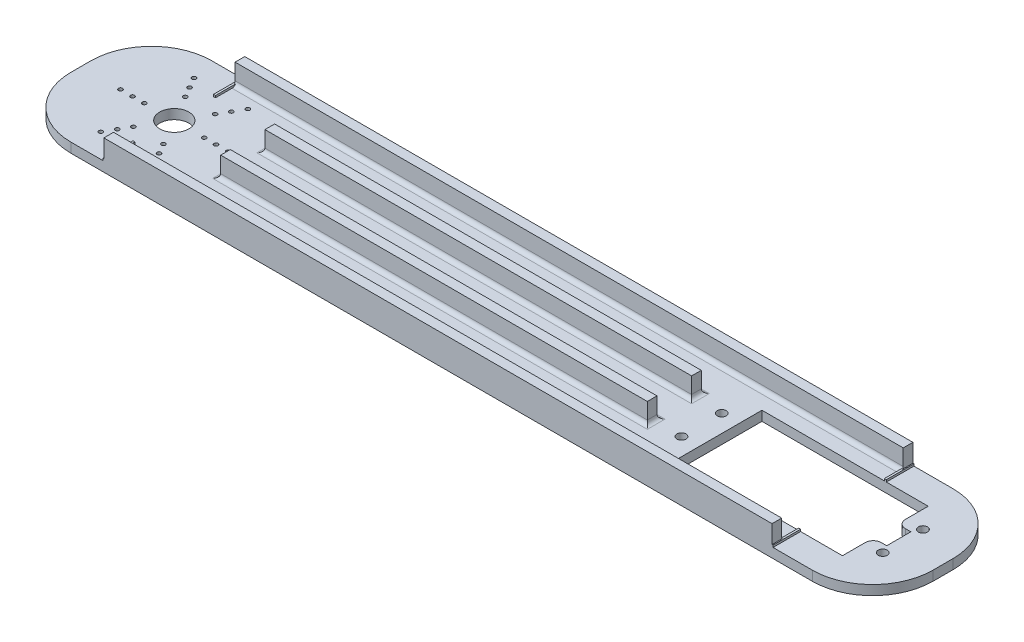
SolidWorks part; units mm, degrees
ref_plane "Front Plane" through (0, 0, 0) normal (0, 0, 1) x (1, 0, 0)
ref_plane "Top Plane" through (0, 0, 0) normal (0, 1, 0) x (1, 0, 0)
ref_plane "Right Plane" through (0, 0, 0) normal (1, 0, 0) x (0, 0, -1)
sketch "Sketch1" plane through (0, 0, 0) normal (0, 1, 0) x (1, 0, 0)
  line L1 (-86.6771, 38.9958) -> (127.5229, 38.9958)
  line L2 (-86.6771, 38.9958) -> (-86.6771, 3.9958)
  line L3 (-86.6771, 3.9958) -> (127.5229, 3.9958)
  line L4 (127.5229, 38.9958) -> (127.5229, 3.9958)
  dimension "D1" = 214.2
  dimension "D2" = 35
extrude "Boss-Extrude1" add sketch "Sketch1" along normal blind 2.4
sketch "Sketch2" plane through (0, 2.4, 0) normal (0, 1, 0) x (1, 0, 0)
  line L0 (-63.4771, 38.9958) -> (-63.4771, 2.4158) construction
  line L1 (127.5229, 38.9958) -> (-86.6771, 38.9958) construction
  line L2 (-86.6771, 21.4958) -> (127.5229, 21.4958) construction
  line L3 (-86.6771, 38.9958) -> (-86.6771, 3.9958) construction
  line L4 (127.5229, 3.9958) -> (127.5229, 38.9958) construction
  line L5 (112.5229, 38.9958) -> (112.5229, 3.9958) construction
  line L6 (-86.6771, 3.9958) -> (127.5229, 3.9958) construction
  line L7 (72.5229, 38.9958) -> (72.5229, 3.9958) construction
  line L9 (72.5229, 31.4958) -> (112.5229, 31.4958)
  line L10 (72.5229, 31.4958) -> (72.5229, 11.4958)
  line L11 (72.5229, 11.4958) -> (112.5229, 11.4958)
  line L12 (112.5229, 31.4958) -> (112.5229, 11.4958)
  circle A0 centre (67.5229, 26.4958) radius 1.13
  circle A1 centre (117.5229, 26.4958) radius 1.13
  circle A2 centre (117.5229, 16.4958) radius 1.13
  circle A3 centre (67.5229, 16.4958) radius 1.13
  circle A4 centre (-63.4771, 21.4958) radius 3.625
  circle A5 centre (-70.9071, 21.4958) radius 0.5
  circle A6 centre (-73.8421, 21.4958) radius 0.5
  circle A7 centre (-76.8471, 21.4958) radius 0.5
  circle A8 centre (-70.1621, 33.0745) radius 0.5
  circle A9 centre (-68.6596, 30.4721) radius 0.5
  circle A10 centre (-67.1921, 27.9303) radius 0.5
  circle A11 centre (-56.7921, 33.0745) radius 0.5
  circle A12 centre (-58.2946, 30.4721) radius 0.5
  circle A13 centre (-59.7621, 27.9303) radius 0.5
  circle A14 centre (-50.1071, 21.4958) radius 0.5
  circle A15 centre (-53.1121, 21.4958) radius 0.5
  circle A16 centre (-56.0471, 21.4958) radius 0.5
  circle A17 centre (-56.7921, 9.917) radius 0.5
  circle A18 centre (-58.2946, 12.5194) radius 0.5
  circle A19 centre (-59.7621, 15.0612) radius 0.5
  circle A20 centre (-70.1621, 9.917) radius 0.5
  circle A21 centre (-68.6596, 12.5194) radius 0.5
  circle A22 centre (-67.1921, 15.0612) radius 0.5
  point P24 (-63.4771, 21.4958)
  point P37 (-86.6771, 21.4958)
  point P39 (-63.4771, 21.4958)
  point P71 (-63.4771, 21.4958)
  dimension "D5" = 2.26
  dimension "D6" = 2.26
  dimension "D11" = 7.25
  dimension "D12" = 7.43
  dimension "D13" = 10.365
  dimension "D14" = 13.37
  dimension "D15" = 1
  dimension "D16" = 1
  dimension "D17" = 1
  dimension "D19" = 20
  dimension "D1" = 23.2
  dimension "D2" = 15
  dimension "D3" = 40
  dimension "D4" = 10
  dimension "D7" = 5
  dimension "D8" = 5
  dimension "D9" = 5
  dimension "D10" = 5
  dimension "D18" = 6
extrude "Cut-Extrude1" cut sketch "Sketch2" against normal blind 2.4
sketch "Sketch4" plane through (0, 2.4, 0) normal (0, 1, 0) x (1, 0, 0)
  line L0 (72.5229, 21.4958) -> (127.5229, 21.4958) construction
  line L1 (72.5229, 31.4958) -> (72.5229, 11.4958) construction
  line L2 (127.5229, 3.9958) -> (127.5229, 38.9958) construction
  line L3 (112.5229, 11.4958) -> (112.5229, 31.4958) construction
  line L4 (112.5229, 24.4958) -> (116.5229, 24.4958)
  line L5 (112.5229, 24.4958) -> (112.5229, 18.4958)
  line L6 (112.5229, 18.4958) -> (116.5229, 18.4958)
  line L7 (116.5229, 24.4958) -> (116.5229, 18.4958)
  dimension "D1" = 6
  dimension "D2" = 3
  dimension "D3" = 4
extrude "Cut-Extrude2" cut sketch "Sketch4" against normal blind 2.4
sketch "Sketch5" plane through (0, 2.4, 0) normal (0, 1, 0) x (1, 0, 0)
  line L0 (-63.4771, 21.4958) -> (127.5229, 21.4958) construction
  line L1 (127.5229, 3.9958) -> (127.5229, 38.9958) construction
  line L2 (-63.4771, 38.9958) -> (-63.4771, 3.9958) construction
  line L3 (127.5229, 38.9958) -> (-86.6771, 38.9958) construction
  line L4 (-86.6771, 3.9958) -> (127.5229, 3.9958) construction
  line L5 (102.5229, 38.9958) -> (102.5229, 3.9958) construction
  line L6 (112.5229, 31.4958) -> (72.5229, 31.4958) construction
  line L7 (102.2729, 38.9958) -> (102.7729, 38.9958)
  line L8 (102.2729, 38.9958) -> (102.2729, 31.4958)
  line L9 (102.2729, 31.4958) -> (102.7729, 31.4958)
  line L10 (102.7729, 38.9958) -> (102.7729, 31.4958)
  line L11 (102.7729, 3.9958) -> (102.7729, 11.4958)
  line L12 (102.2729, 11.4958) -> (102.7729, 11.4958)
  line L13 (102.2729, 3.9958) -> (102.2729, 11.4958)
  line L14 (102.2729, 3.9958) -> (102.7729, 3.9958)
  line L15 (-63.2271, 3.9958) -> (-63.2271, 11.4958)
  line L16 (-63.7271, 38.9958) -> (-63.2271, 38.9958)
  line L17 (-63.7271, 38.9958) -> (-63.7271, 31.4958)
  line L18 (-63.7271, 31.4958) -> (-63.2271, 31.4958)
  line L19 (-63.2271, 38.9958) -> (-63.2271, 31.4958)
  line L20 (-63.7271, 11.4958) -> (-63.2271, 11.4958)
  line L21 (-63.7271, 3.9958) -> (-63.7271, 11.4958)
  line L22 (-63.7271, 3.9958) -> (-63.2271, 3.9958)
  dimension "D1" = 166
  dimension "D2" = 0.5
  dimension "D3" = 0.25
  dimension "D4" = 0.25
  dimension "D5" = 0.5
  dimension "D6" = 7.5
extrude "Boss-Extrude2" add sketch "Sketch5" along normal blind 0.5
sketch "Sketch7" plane through (0, 2.4, 0) normal (0, 1, 0) x (1, 0, 0)
  line L0 (71.8729, 32.1458) -> (71.8729, 10.8458)
  line L1 (72.5229, 31.4958) -> (112.5229, 31.4958)
  line L2 (72.5229, 31.4958) -> (72.5229, 11.4958)
  line L3 (72.5229, 11.4958) -> (112.5229, 11.4958)
  line L4 (112.5229, 31.4958) -> (112.5229, 11.4958)
  line L5 (71.8729, 10.8458) -> (113.1729, 10.8458)
  line L6 (113.1729, 32.1458) -> (113.1729, 10.8458)
  line L7 (71.8729, 32.1458) -> (113.1729, 32.1458)
  dimension "D1" = 0.65
extrude "Cut-Extrude3" cut sketch "Sketch7" against normal through all both and the other way through all
sketch "Sketch8" plane through (0, 2.4, 0) normal (0, 1, 0) x (1, 0, 0)
  line L0 (102.5229, 38.9958) -> (102.5229, 3.9958) construction
  line L1 (-63.4771, 38.9958) -> (102.5229, 38.9958)
  line L2 (-63.4771, 38.9958) -> (-63.4771, 36.5958)
  line L3 (-63.4771, 36.5958) -> (102.5229, 36.5958)
  line L4 (102.5229, 38.9958) -> (102.5229, 36.5958)
  line L5 (-45.2566, 3.9958) -> (-45.2566, 38.9958) construction
  line L6 (-63.2271, 3.9958) -> (102.2729, 3.9958) construction
  line L7 (-63.4771, 21.4958) -> (116.5229, 21.4958) construction
  line L8 (-45.2566, 28.1958) -> (60.7434, 28.1958)
  line L9 (-45.2566, 28.1958) -> (-45.2566, 25.7958)
  line L10 (-45.2566, 25.7958) -> (60.7434, 25.7958)
  line L11 (60.7434, 28.1958) -> (60.7434, 25.7958)
  line L12 (116.5229, 18.4958) -> (116.5229, 24.4958) construction
  line L13 (60.7434, 14.7958) -> (60.7434, 17.1958)
  line L14 (-45.2566, 17.1958) -> (60.7434, 17.1958)
  line L15 (-45.2566, 14.7958) -> (-45.2566, 17.1958)
  line L16 (-45.2566, 14.7958) -> (60.7434, 14.7958)
  line L17 (102.5229, 3.9958) -> (102.5229, 6.3958)
  line L18 (-63.4771, 6.3958) -> (102.5229, 6.3958)
  line L19 (-63.4771, 3.9958) -> (-63.4771, 6.3958)
  line L20 (-63.4771, 3.9958) -> (102.5229, 3.9958)
  dimension "D1" = 2.4
  dimension "D2" = 2.4
  dimension "D3" = 106
  dimension "D4" = 8.4
extrude "Boss-Extrude3" add sketch "Sketch8" along normal blind 5
fillet "Fillet1" radius 15 4 edges at (127.5229, 1.2, -3.9958) (127.5229, 1.2, -38.9958) (-86.6771, 1.2, -3.9958) (-86.6771, 1.2, -38.9958)
fillet "Fillet2" radius 2 2 edges at (113.1729, 1.2, -18.4958) (113.1729, 1.2, -24.4958)
fillet "Fillet3" radius 1 10 edges at (19.5229, 2.4, -6.3958) (60.7434, 2.4, -15.9958) (7.7434, 2.4, -17.1958) (60.7434, 2.4, -26.9958) (7.7434, 2.4, -28.1958) (7.7434, 2.4, -14.7958) (-45.2566, 2.4, -15.9958) (-45.2566, 2.4, -26.9958) (7.7434, 2.4, -25.7958) (19.5229, 2.4, -36.5958)
